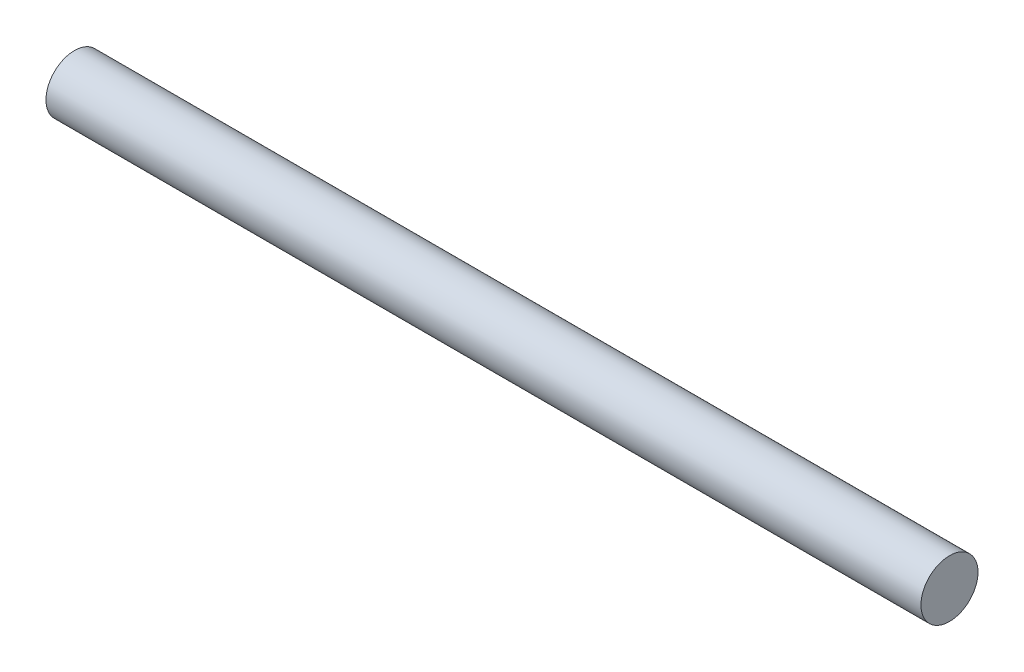
SolidWorks part; units mm, degrees
ref_plane "Front Plane" through (0, 0, 0) normal (0, 0, 1) x (1, 0, 0)
ref_plane "Top Plane" through (0, 0, 0) normal (0, 1, 0) x (1, 0, 0)
ref_plane "Right Plane" through (0, 0, 0) normal (1, 0, 0) x (0, 0, -1)
sketch "Sketch1" plane through (0, 0, 0) normal (1, 0, 0) x (0, 0, -1)
  circle A0 centre (0, 0) radius 1.5
  dimension "D1" = 3
extrude "Boss-Extrude1" add sketch "Sketch1" along normal blind 46
